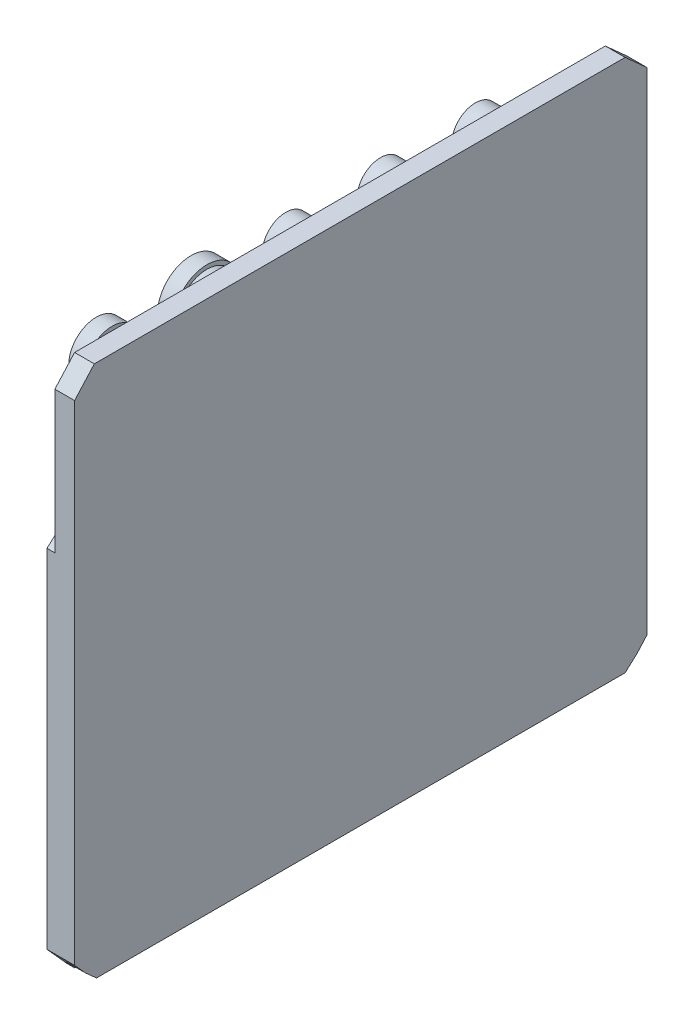
SolidWorks part; units mm, degrees
ref_plane "正面" through (0, 0, 0) normal (0, 0, 1) x (1, 0, 0)
ref_plane "平面" through (0, 0, 0) normal (0, 1, 0) x (1, 0, 0)
ref_plane "右側面" through (0, 0, 0) normal (1, 0, 0) x (0, 0, -1)
sketch "ｽｹｯﾁ1" plane through (0, 0, 0) normal (1, 0, 0) x (0, 0, -1)
  line L1 (0, 0) -> (145, 0)
  line L2 (0, 0) -> (0, 135)
  line L3 (0, 135) -> (145, 135)
  line L4 (145, 0) -> (145, 135)
  dimension "D1" = 135
  dimension "D2" = 145
extrude "押し出し1" add sketch "ｽｹｯﾁ1" along normal blind 5
chamfer "面取り1" distance 5 angle 48 4 edges at (2.5, 0, 0) (2.5, 0, -145) (2.5, 135, -145) (2.5, 135, 0)
sketch "ｽｹｯﾁ2" plane through (0, 0, 0) normal (-1, 0, 0) x (0, 0, 1)
  line L0 (-145, 5.5531) -> (-145, 130) construction
  line L1 (-145, 98.5429) -> (0, 98.5429)
  line L2 (-145, 98.5429) -> (-145, 0)
  line L3 (-145, 0) -> (0, 0)
  line L4 (0, 98.5429) -> (0, 0)
extrude "押し出し2" add sketch "ｽｹｯﾁ2" along normal blind 2
chamfer "面取り2" distance 5 angle 48 4 edges at (-1, 0, -145) (-1, 0, 0)
sketch "ｽｹｯﾁ3" plane through (0, 0, 0) normal (-1, 0, 0) x (0, 0, 1)
  line L0 (-151.9856, 119) -> (13.2038, 119) construction
  line L1 (-139.4469, 135) -> (-5, 135) construction
  line L2 (-120.5, 129.5474) -> (-120.5, 110.6222) construction
  line L3 (-96.5, 127.3845) -> (-96.5, 110.6222) construction
  line L4 (-72.5, 127.3845) -> (-72.5, 110.6222) construction
  line L5 (-48.5, 127.3845) -> (-48.5, 110.6222) construction
  line L6 (-24.5, 127.3845) -> (-24.5, 110.6222) construction
  line L7 (-145, 92.9898) -> (-145, 130) construction
  circle A0 centre (-120.5, 119) radius 5
  circle A1 centre (-96.5, 119.0034) radius 5
  circle A2 centre (-72.5, 119) radius 5
  circle A3 centre (-48.5, 119) radius 7.5
  circle A4 centre (-24.5, 119.0034) radius 6
  dimension "D7" = 10
  dimension "D8" = 10
  dimension "D9" = 10
  dimension "D10" = 15
  dimension "D11" = 12
  dimension "D1" = 16
  dimension "D2" = 24.5
  dimension "D3" = 24
  dimension "D4" = 24
  dimension "D5" = 24
  dimension "D6" = 24
extrude "押し出し3" add sketch "ｽｹｯﾁ3" along normal blind 10
sketch "ｽｹｯﾁ4" plane through (-2, 0, 0) normal (-1, 0, 0) x (0, 0, 1)
  line L0 (-159.5097, 40) -> (18.7797, 40) construction
  line L1 (-139.4469, 0) -> (-5, 0) construction
  line L2 (-100, 55.1204) -> (-100, 29.1551) construction
  line L3 (-45, 55.1204) -> (-45, 29.1551) construction
  line L4 (-145, 92.9898) -> (-145, 5) construction
  line L5 (0, 5.5531) -> (0, 93.5429) construction
  circle A0 centre (-100, 40) radius 20
  circle A1 centre (-45, 40) radius 20
  dimension "D4" = 40
  dimension "D5" = 40
  dimension "D1" = 40
  dimension "D2" = 55
  dimension "D3" = 45
sketch "ｽｹｯﾁ7" plane through (-10, 0, 0) normal (-1, 0, 0) x (0, 0, 1)
  circle A0 centre (-120.5, 119) radius 6
  circle A1 centre (-96.5, 119.0034) radius 6
  circle A2 centre (-72.5, 119) radius 6
  circle A3 centre (-48.5, 119) radius 8.5
  circle A4 centre (-24.5, 119.0034) radius 7
  circle A5 centre (-120.5, 119) radius 4
  circle A6 centre (-96.5, 119.0034) radius 4
  circle A7 centre (-72.5, 119) radius 4
  circle A8 centre (-48.5, 119) radius 6.5
  circle A9 centre (-24.5, 119.0034) radius 4
  dimension "D1" = 12
  dimension "D2" = 12
  dimension "D3" = 12
  dimension "D4" = 17
  dimension "D5" = 14
  dimension "D6" = 8
  dimension "D7" = 8
  dimension "D8" = 8
  dimension "D9" = 13
  dimension "D10" = 8
extrude "押し出し6" add sketch "ｽｹｯﾁ7" along normal blind 4
